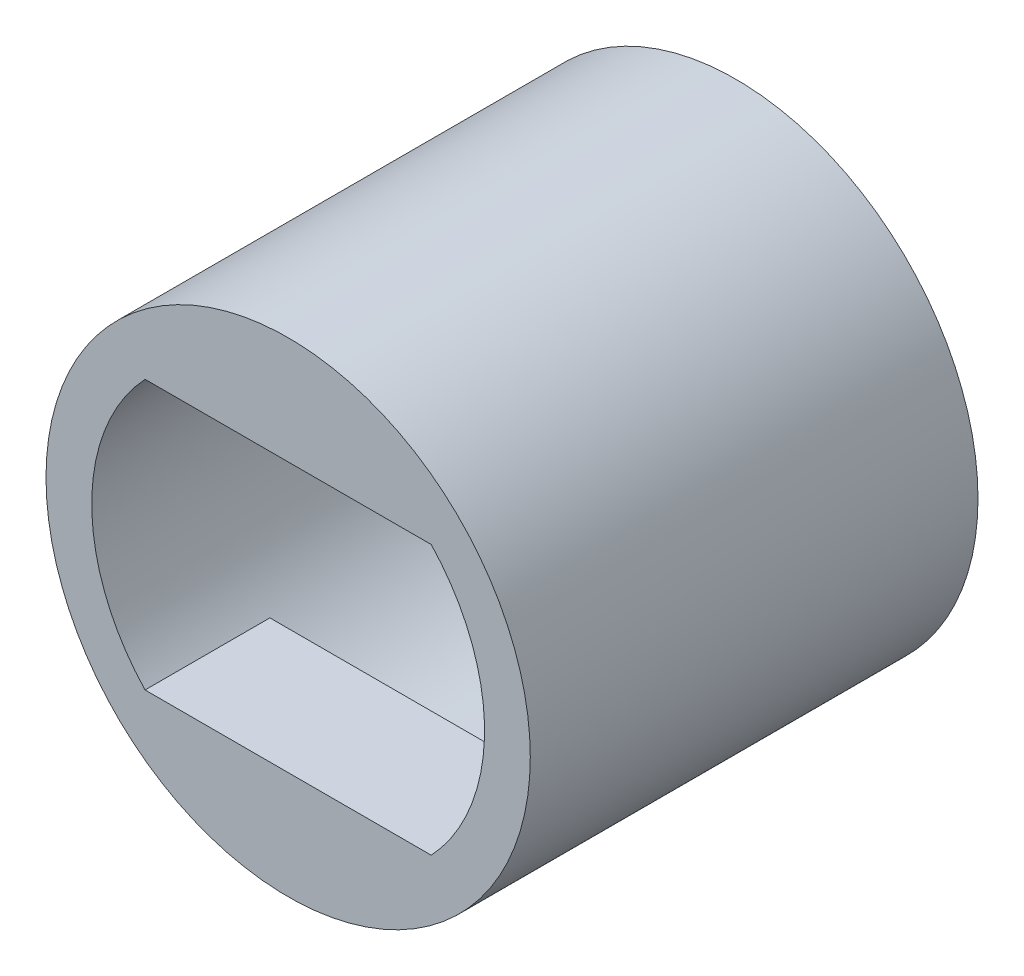
SolidWorks part; units mm, degrees
material "ABS"
ref_plane "Alzado" through (0, 0, 0) normal (0, 0, 1) x (1, 0, 0)
ref_plane "Planta" through (0, 0, 0) normal (0, 1, 0) x (1, 0, 0)
ref_plane "Vista lateral" through (0, 0, 0) normal (1, 0, 0) x (0, 0, -1)
sketch "Croquis1" plane through (0, 0, 0) normal (0, 0, 1) x (1, 0, 0)
  circle A0 centre (0, 0) radius 22.5
  circle A1 centre (0, 0) radius 18.25
  dimension "D1" = 45
  dimension "D2" = 36.5
extrude "Saliente-Extruir1" add sketch "Croquis1" along normal blind 30
sketch "Croquis2" plane through (0, 0, 30) normal (0, 0, 1) x (1, 0, 0)
  line L0 (-18.7083, 12.5) -> (18.7083, 12.5)
  line L1 (-18.7083, -12.5) -> (18.7083, -12.5)
  line L2 (0, -12.5) -> (0, 12.5) construction
  circle A0 centre (0, 0) radius 22.5 construction
  arc A1 (-18.7083, -12.5) -> (18.7083, -12.5) centre (0, 0) ccw
  arc A2 (18.7083, 12.5) -> (-18.7083, 12.5) centre (0, 0) ccw
  point P10 (0, 0)
  dimension "D1" = 25
extrude "Saliente-Extruir2" add sketch "Croquis2" along normal blind 11.6
sketch "Croquis3" plane through (0, 0, 30) normal (0, 0, 1) x (1, 0, 0)
  line L0 (18.7083, 12.5) -> (13.2971, 12.5) construction
  line L1 (13.2971, -12.5) -> (18.7083, -12.5) construction
  line L2 (-13.2971, 12.5) -> (-18.7083, 12.5) construction
  line L3 (-18.7083, -12.5) -> (-13.2971, -12.5) construction
  line L4 (18.7083, 12.5) -> (13.2971, 12.5)
  line L5 (13.2971, -12.5) -> (18.7083, -12.5)
  line L6 (-13.2971, 12.5) -> (-18.7083, 12.5)
  line L7 (-18.7083, -12.5) -> (-13.2971, -12.5)
  arc A0 (13.2971, -12.5) -> (13.2971, 12.5) centre (0, 0) ccw construction
  arc A1 (18.7083, -12.5) -> (18.7083, 12.5) centre (0, 0) ccw construction
  arc A2 (-18.7083, 12.5) -> (-18.7083, -12.5) centre (0, 0) ccw construction
  arc A3 (-13.2971, 12.5) -> (-13.2971, -12.5) centre (0, 0) ccw construction
  arc A4 (13.2971, -12.5) -> (13.2971, 12.5) centre (0, 0) ccw
  arc A5 (18.7083, -12.5) -> (18.7083, 12.5) centre (0, 0) ccw
  arc A6 (-18.7083, 12.5) -> (-18.7083, -12.5) centre (0, 0) ccw
  arc A7 (-13.2971, 12.5) -> (-13.2971, -12.5) centre (0, 0) ccw
extrude "Saliente-Extruir3" add sketch "Croquis3" along normal up to surface (11.6 mm away) up to face at (0, 17.5, 41.6)
